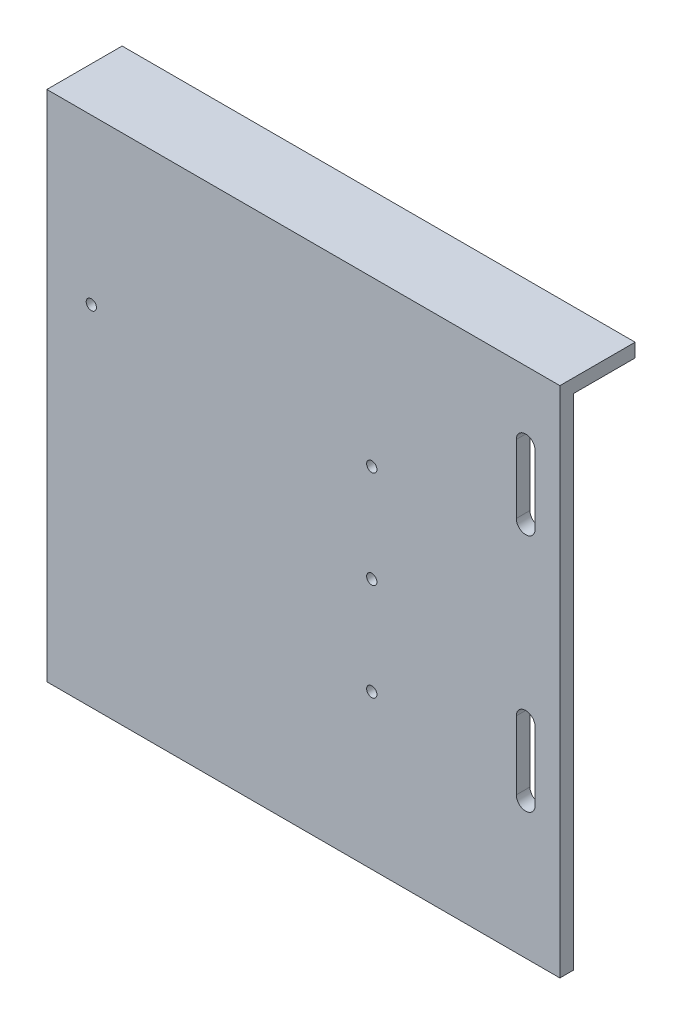
SolidWorks part; units mm, degrees
ref_plane "前视基准面" through (0, 0, 0) normal (0, 0, 1) x (1, 0, 0)
ref_plane "上视基准面" through (0, 0, 0) normal (0, 1, 0) x (1, 0, 0)
ref_plane "右视基准面" through (0, 0, 0) normal (1, 0, 0) x (0, 0, -1)
other "Configuration Table"
sketch "草图1" plane through (0, 0, 0) normal (0, 0, 1) x (1, 0, 0)
  line L0 (140, 130) -> (140, 110) construction
  line L1 (0, 0) -> (150, 0)
  line L2 (0, 0) -> (0, 150)
  line L3 (0, 150) -> (150, 150)
  line L4 (150, 0) -> (150, 150)
  line L5 (142.75, 130) -> (142.75, 110)
  line L6 (137.25, 130) -> (137.25, 110)
  line L7 (140, 60) -> (140, 40) construction
  line L8 (142.75, 60) -> (142.75, 40)
  line L9 (137.25, 60) -> (137.25, 40)
  arc A0 (142.75, 130) -> (137.25, 130) centre (140, 130) ccw
  arc A1 (137.25, 110) -> (142.75, 110) centre (140, 110) ccw
  arc A2 (142.75, 60) -> (137.25, 60) centre (140, 60) ccw
  arc A3 (137.25, 40) -> (142.75, 40) centre (140, 40) ccw
  circle A4 centre (95, 102) radius 1.5
  circle A5 centre (95, 45) radius 1.5
  circle A6 centre (95, 73.5) radius 1.5
  circle A7 centre (13, 102) radius 1.5
  point P7 (140, 120)
  point P12 (140, 50)
  dimension "D10" = 57
  dimension "D11" = 3
  dimension "D12" = 3
  dimension "D13" = 28.5
  dimension "D15" = 82
  dimension "D1" = 150
  dimension "D2" = 150
  dimension "D3" = 10
  dimension "D4" = 5.5
  dimension "D5" = 5.5
  dimension "D6" = 20
  dimension "D7" = 40
  dimension "D8" = 20
  dimension "D9" = 20
  dimension "D14" = 45
  dimension "D16" = 95
extrude "凸台-拉伸1" add sketch "草图1" along normal blind 4
sketch "草图2" plane through (0, 0, 0) normal (0, 0, -1) x (-1, 0, 0)
  line L0 (0, 150) -> (0, 0) construction
  line L1 (-150, 150) -> (0, 150)
  line L2 (-150, 150) -> (-150, 146)
  line L3 (-150, 146) -> (0, 146)
  line L4 (0, 150) -> (0, 146)
  dimension "D1" = 4
extrude "凸台-拉伸2" add sketch "草图2" along normal blind 18
